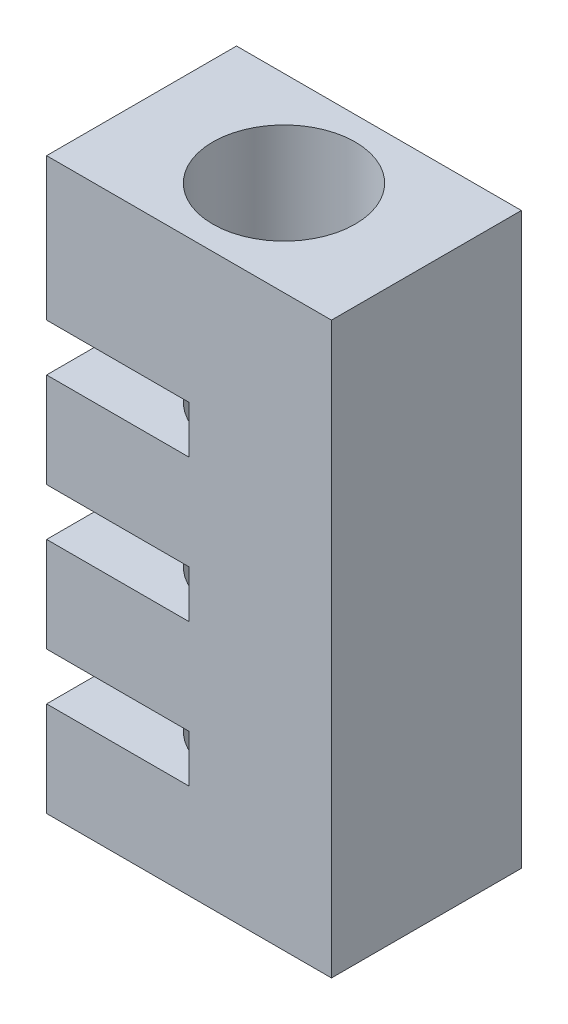
SolidWorks part; units mm, degrees
ref_plane "Front Plane" through (0, 0, 0) normal (0, 0, 1) x (1, 0, 0)
ref_plane "Top Plane" through (0, 0, 0) normal (0, 1, 0) x (1, 0, 0)
ref_plane "Right Plane" through (0, 0, 0) normal (1, 0, 0) x (0, 0, -1)
sketch "Sketch1" plane through (0, 0, 0) normal (0, 0, 1) x (1, 0, 0)
  line L0 (0, 0) -> (30, 0)
  line L1 (30, 0) -> (30, 60)
  line L2 (30, 60) -> (0, 60)
  line L3 (0, 60) -> (0, 45)
  line L4 (0, 45) -> (15, 45)
  line L5 (15, 45) -> (15, 40)
  line L6 (15, 40) -> (0, 40)
  line L7 (0, 40) -> (0, 30)
  line L8 (0, 30) -> (15, 30)
  line L9 (15, 30) -> (15, 25)
  line L10 (15, 25) -> (0, 25)
  line L11 (0, 25) -> (0, 15)
  line L12 (0, 15) -> (15, 15)
  line L13 (15, 15) -> (15, 10)
  line L14 (15, 10) -> (0, 10)
  line L15 (0, 10) -> (0, 0)
  dimension "D1" = 60
  dimension "D2" = 5
  dimension "D3" = 5
  dimension "D4" = 5
  dimension "D5" = 10
  dimension "D6" = 10
  dimension "D7" = 10
  dimension "D8" = 15
  dimension "D9" = 30
  dimension "D10" = 15
  dimension "D11" = 15
  dimension "D12" = 15
extrude "Boss-Extrude1" add sketch "Sketch1" along normal blind 20
sketch "Sketch4" plane through (0, 60, 0) normal (0, 1, 0) x (1, 0, 0)
  line L0 (0, -20) -> (0, 0) construction
  line L2 (30, 0) -> (0, 0) construction
  circle A0 centre (15, -10) radius 7.5
  dimension "D1" = 15
  dimension "D2" = 15
  dimension "D3" = 10
extrude "Cut-Extrude1" cut sketch "Sketch4" against normal through all
